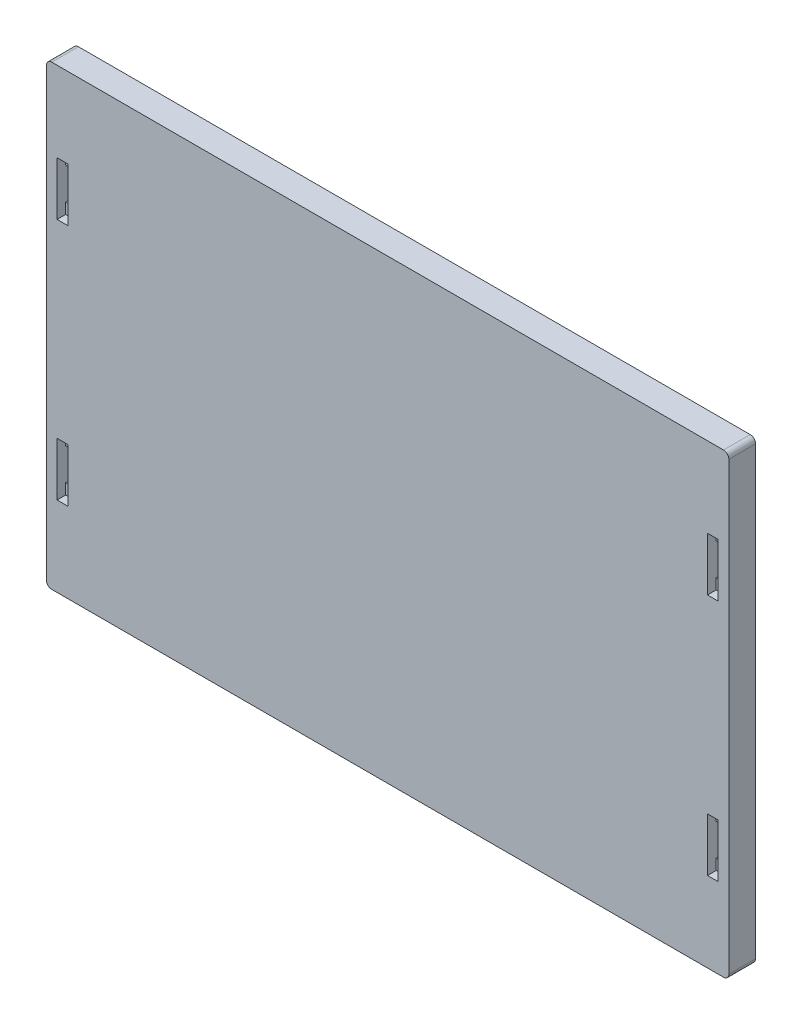
SolidWorks part; units mm, degrees
ref_plane "Front Plane" through (0, 0, 0) normal (0, 0, 1) x (1, 0, 0)
ref_plane "Top Plane" through (0, 0, 0) normal (0, 1, 0) x (1, 0, 0)
ref_plane "Right Plane" through (0, 0, 0) normal (1, 0, 0) x (0, 0, -1)
sketch "Sketch1" plane through (0, 0, 0) normal (0, 0, 1) x (1, 0, 0)
  line L1 (-54.6738, 25.2702) -> (73.0862, 25.2702)
  line L2 (-54.6738, 25.2702) -> (-54.6738, -60.2098)
  line L3 (-54.6738, -60.2098) -> (73.0862, -60.2098)
  line L4 (73.0862, 25.2702) -> (73.0862, -60.2098)
  dimension "D1" = 127.76
  dimension "D2" = 85.48
extrude "Boss-Extrude1" add sketch "Sketch1" along normal blind 5
sketch "Sketch3" plane through (0, 0, 5) normal (0, 0, 1) x (1, 0, 0)
  line L0 (-54.6738, 25.2702) -> (-54.6738, -60.2098) construction
  line L1 (-50.6738, 0.2702) -> (-52.6738, 0.2702)
  line L2 (-50.6738, 0.2702) -> (-50.6738, 10.2702)
  line L3 (-50.6738, 10.2702) -> (-52.6738, 10.2702)
  line L4 (-52.6738, 0.2702) -> (-52.6738, 10.2702)
  line L5 (-50.6738, 0.2702) -> (-52.6738, 10.2702) construction
  line L6 (-50.6738, 10.2702) -> (-52.6738, 0.2702) construction
  line L7 (73.0862, 25.2702) -> (-54.6738, 25.2702) construction
  point P0 (-51.6738, 5.2702)
  dimension "D1" = 2
  dimension "D2" = 2
  dimension "D3" = 20
  dimension "D4" = 10
extrude "Cut-Extrude2" cut sketch "Sketch3" against normal offset from surface (1.6 mm away) 1.6 up to face at (9.2062, -17.4698, 5)
sketch "Sketch4" plane through (0, 0, 3.4) normal (0, 0, 1) x (1, 0, 0)
  line L0 (-52.6738, 10.2702) -> (-52.6738, 0.2702) construction
  line L1 (-50.6738, 2.2702) -> (-52.6738, 2.2702)
  line L2 (-50.6738, 2.2702) -> (-50.6738, 8.2702)
  line L3 (-50.6738, 8.2702) -> (-52.6738, 8.2702)
  line L4 (-52.6738, 2.2702) -> (-52.6738, 8.2702)
  line L5 (-50.6738, 2.2702) -> (-52.6738, 8.2702) construction
  line L6 (-50.6738, 8.2702) -> (-52.6738, 2.2702) construction
  line L7 (-50.6738, 10.2702) -> (-50.6738, 0.2702) construction
  point P0 (-51.6738, 5.2702)
  point P9 (-50.6738, 5.2702)
  dimension "D1" = 6
  dimension "D2" = 0
extrude "Cut-Extrude3" cut sketch "Sketch4" against normal through all
ref_plane "Plane1" through (9.2062, 0, 0) normal (-1, 0, 0) x (0, 0, 1)
ref_plane "Plane2" through (0, -17.4698, 0) normal (0, 1, 0) x (1, 0, 0)
mirror "Mirror1" about plane through (9.2062, 0, 0) normal (-1, 0, 0) of "Cut-Extrude3", "Cut-Extrude2"
mirror "Mirror2" about plane through (0, -17.4698, 0) normal (0, 1, 0) of "Mirror1", "Cut-Extrude2", "Cut-Extrude3"
sketch "Sketch6" plane through (0, 0, 0) normal (0, 0, -1) x (-1, 0, 0)
  line L0 (54.6738, -60.2098) -> (-73.0862, -60.2098) construction
  line L1 (54.6738, 25.2702) -> (54.6738, -60.2098) construction
  circle A0 centre (-9.2062, -17.4698) radius 12.75
  point P4 (-9.2062, -60.2098)
  point P7 (54.6738, -17.4698)
  dimension "D3" = 25.5
  dimension "D1" = 0
  dimension "D2" = 0
extrude "Cut-Extrude4" cut sketch "Sketch6" against normal offset from surface (4.4 mm away) 0.6 up to face at (70.0862, -40.2098, 5)
fillet "Fillet1" radius 1 4 edges at (73.0862, 25.2702, 2.5) (-54.6738, 25.2702, 2.5) (-54.6738, -60.2098, 2.5) (73.0862, -60.2098, 2.5)
equation "\"platewidth\"=127.76"
equation "\"D1@Sketch1\"=\"platewidth\""
equation "\"plateheight\"=85.48"
equation "\"D2@Sketch1\"=\"plateheight\""
equation "\"od\"= \"od_meas\" + \"od_offset\""
equation "\"height\"= \"height_overall\" - \"neck_offset\""
equation "\"minspacing\"= 4'min padding between vials"
equation "\"nx\"= int ( ( \"platewidth\" - \"minspacing\" ) / ( \"od\" + \"minspacing\" ) )'force spacing on left and right ends"
equation "\"ny\"= int ( ( \"plateheight\" - \"minspacing\" ) / ( \"od\" + \"minspacing\" ) )"
equation "\"xspacing\"= ( \"platewidth\" - ( \"nx\" * \"od\" ) ) / ( \"nx\" + 1 )"
equation "\"yspacing\"= ( \"plateheight\" - ( \"ny\" * \"od\" ) ) / ( \"ny\" + 1 )"
equation "\"od_offset\"= 0.6'extra width to print vial holes"
equation "\"od_meas\"= 14.65'measured vial outer dimension (mm)"
equation "\"neck_offset\"= 9'distance from top of threads to wide point of vial"
equation "\"height_overall\"= 46.9'overall height of vial"
equation "\"xpitch\"= \"od\" + \"xspacing\"'center to center distance of wells"
equation "\"ypitch\"= \"od\" + \"yspacing\""
